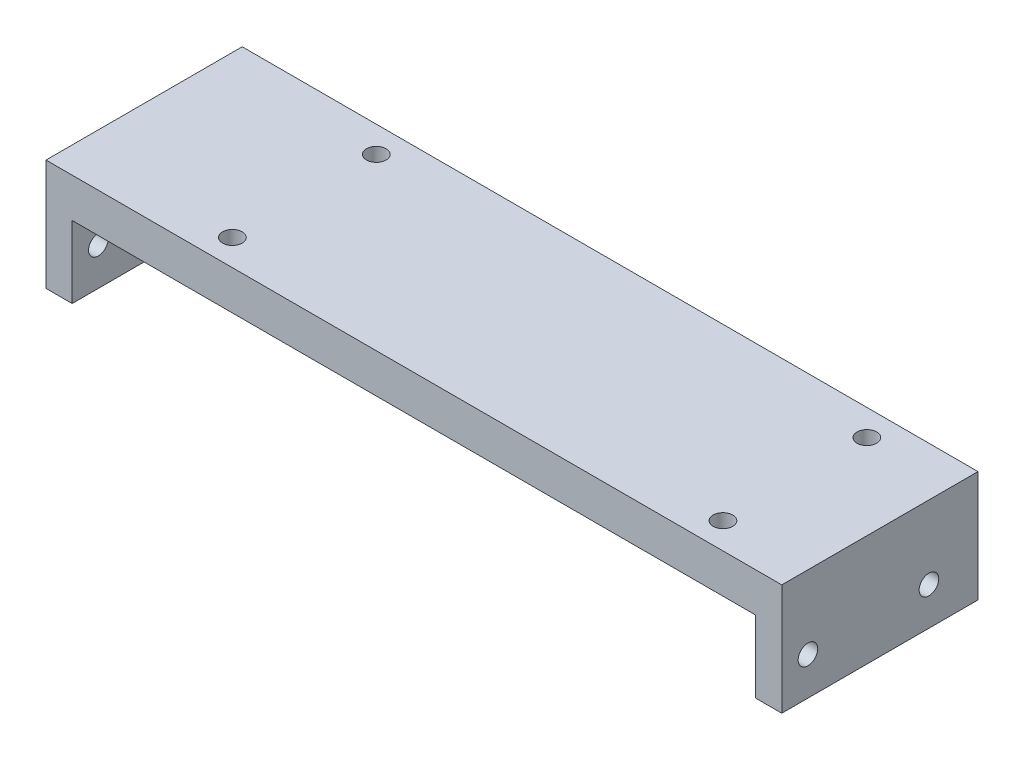
SolidWorks part; units mm, degrees
ref_plane "前视基准面" through (0, 0, 0) normal (0, 0, 1) x (1, 0, 0)
ref_plane "上视基准面" through (0, 0, 0) normal (0, 1, 0) x (1, 0, 0)
ref_plane "右视基准面" through (0, 0, 0) normal (1, 0, 0) x (0, 0, -1)
sketch "草图1" plane through (0, 0, 0) normal (0, 1, 0) x (1, 0, 0)
  line L0 (-52.25, 15) -> (-52.25, -15)
  line L1 (-52.25, 15) -> (52.25, 15)
  line L2 (-52.25, -15) -> (52.25, -15)
  line L3 (52.25, 15) -> (52.25, -15)
  line L4 (0, -15) -> (0, 15) construction
  line L5 (-52.25, 0) -> (52.25, 0) construction
  circle A0 centre (-31.75, 11) radius 1.5
  circle A2 centre (43.25, 11) radius 1.5
  circle A4 centre (43.25, -11) radius 1.5
  circle A5 centre (-31.75, -11) radius 1.5
  point P1 (0, 0)
  dimension "D3" = 3
  dimension "D1" = 30
  dimension "D2" = 20.5
  dimension "D4" = 104.5
  dimension "D5" = 75
  dimension "D6" = 11
extrude "凸台-拉伸1" add sketch "草图1" along normal blind 6
sketch "草图2" plane through (-52.25, 0, 0) normal (-1, 0, 0) x (0, 0, 1)
  line L0 (-15, 6) -> (-15, 0) construction
  line L1 (15, 6) -> (-15, 6)
  line L2 (15, 6) -> (15, -11)
  line L3 (15, -11) -> (-15, -11)
  line L4 (-15, 6) -> (-15, -11)
  line L5 (0, 6) -> (0, -11) construction
  circle A0 centre (11, -5.2) radius 1.5
  circle A1 centre (-11, -5.2) radius 1.5
  dimension "D4" = 3
  dimension "D1" = 17
  dimension "D2" = 4
  dimension "D3" = 11.2
extrude "凸台-拉伸2" add sketch "草图2" along normal blind 4
sketch "草图3" plane through (52.25, 0, 0) normal (1, 0, 0) x (0, 0, -1)
  line L0 (-15, 6) -> (-15, 0) construction
  line L1 (15, 6) -> (-15, 6)
  line L2 (15, 6) -> (15, -11)
  line L3 (15, -11) -> (-15, -11)
  line L4 (-15, 6) -> (-15, -11)
  line L5 (15, -11) -> (-15, -11) construction
  circle A0 centre (-11, -5.2) radius 1.5
  circle A1 centre (-11, -5.2) radius 1.5 construction
  circle A2 centre (7.5, -5.2) radius 1.5
  dimension "D1" = 7.5
extrude "凸台-拉伸3" add sketch "草图3" along normal blind 4
